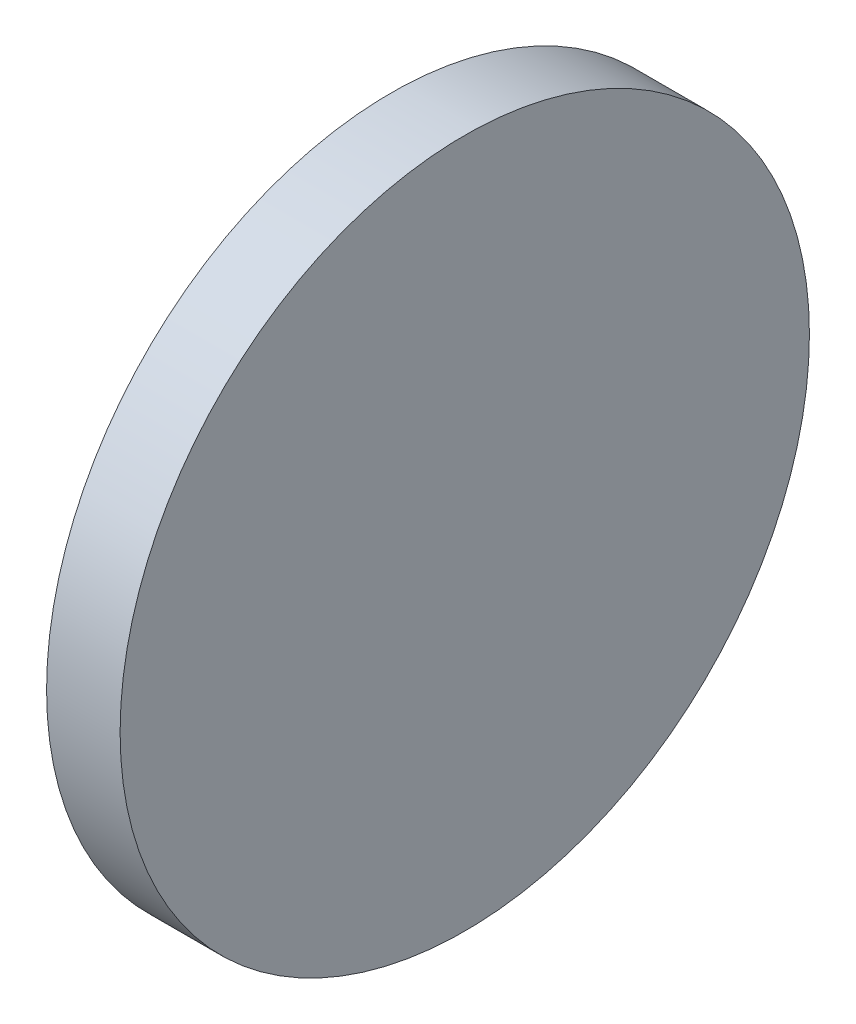
SolidWorks part; units mm, degrees
ref_plane "Front Plane" through (0, 0, 0) normal (0, 0, 1) x (1, 0, 0)
ref_plane "Top Plane" through (0, 0, 0) normal (0, 1, 0) x (1, 0, 0)
ref_plane "Right Plane" through (0, 0, 0) normal (1, 0, 0) x (0, 0, -1)
sketch "Sketch1" plane through (0, 0, 0) normal (1, 0, 0) x (0, 0, -1)
  circle A0 centre (0, 30) radius 7.5
extrude "Board" add sketch "Sketch1" along normal blind 1.6 from offset 71.8
